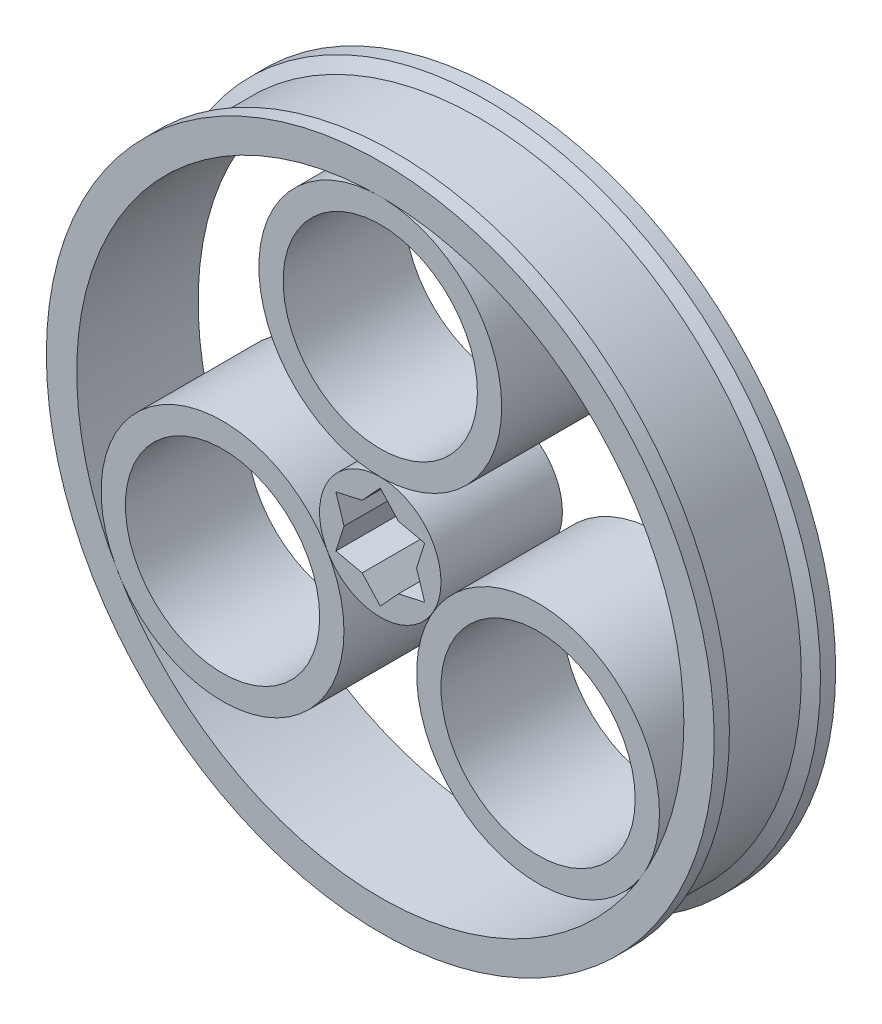
SolidWorks part; units mm, degrees
ref_plane "Front Plane" through (0, 0, 0) normal (0, 0, 1) x (1, 0, 0)
ref_plane "Top Plane" through (0, 0, 0) normal (0, 1, 0) x (1, 0, 0)
ref_plane "Right Plane" through (0, 0, 0) normal (1, 0, 0) x (0, 0, -1)
sketch "Sketch1" plane through (0, 0, 0) normal (0, 0, 1) x (1, 0, 0)
  circle A0 centre (0, 0) radius 27.5
  circle A1 centre (0, 0) radius 25
  circle A2 centre (0, 0) radius 5
  circle A3 centre (0, 15) radius 10
  circle A5 centre (0, 15) radius 8
  circle A6 centre (12.9904, -7.5) radius 10
  circle A7 centre (12.9904, -7.5) radius 8
  circle A8 centre (-12.9904, -7.5) radius 10
  circle A9 centre (-12.9904, -7.5) radius 8
  point P7 (0, 0)
  point P11 (0, 0)
  point P12 (0, 0)
  point P21 (0, 0)
  dimension "D1" = 55
  dimension "D2" = 50
  dimension "D3" = 10
  dimension "D4" = 2
  dimension "D5" = 3
extrude "Boss-Extrude1" add sketch "Sketch1" along normal blind 10 contours A3 A5 | A8 A9 | A6 A7 | A0 A1 | A2
sketch "Sketch2" plane through (0, 0, 0) normal (0, 0, -1) x (-1, 0, 0)
  line L0 (0, 0) -> (0, 5) construction
  line L1 (0, 3.9225) -> (-1.9538, 1.7903)
  line L2 (0, 3.9225) -> (1.9538, 1.7903)
  line L3 (3.397, 1.9612) -> (2.5273, -0.7969)
  line L4 (3.397, 1.9612) -> (0.5736, 2.5872)
  line L5 (3.397, -1.9612) -> (0.5736, -2.5872)
  line L6 (3.397, -1.9612) -> (2.5273, 0.7969)
  line L7 (0, -3.9225) -> (-1.9538, -1.7903)
  line L8 (0, -3.9225) -> (1.9538, -1.7903)
  line L9 (-3.397, -1.9612) -> (-2.5273, 0.7969)
  line L10 (-3.397, -1.9612) -> (-0.5736, -2.5872)
  line L11 (-3.397, 1.9612) -> (-0.5736, 2.5872)
  line L12 (-3.397, 1.9612) -> (-2.5273, -0.7969)
  circle A1 centre (0, 0) radius 2.65
  circle A2 centre (0, 15) radius 10 construction
  point P1 (-4.6486, -2.2417)
  point P13 (0, 0)
  point P28 (0, 0)
  dimension "D2" = 5.3
  dimension "D3" = 6
  dimension "D1" = 85
extrude "Cut-Extrude1" cut sketch "Sketch2" against normal blind 10
sketch "Sketch3" plane through (0, 0, 0) normal (1, 0, 0) x (0, 0, -1)
  line L0 (-10, -27.5) -> (0, -27.5) construction
  line L1 (-10, 27.5) -> (-8.75, 27.5) construction
  line L2 (-10, 27.5) -> (-10, -27.5) construction
  line L3 (-10, -27.5) -> (-8.75, -27.5) construction
  line L4 (-8.75, 27.5) -> (-8.75, -27.5) construction
  line L5 (-5, 27.5) -> (-5, -27.5) construction
  line L6 (0, 27.5) -> (-10, 27.5) construction
  line L7 (-1.25, 27.5) -> (-1.25, -27.5) construction
  line L8 (0, -27.5) -> (-1.25, -27.5) construction
  line L9 (0, 27.5) -> (0, -27.5) construction
  line L10 (0, 27.5) -> (-1.25, 27.5) construction
  line L11 (-8.75, 26.5) -> (-1.25, 26.5)
  line L12 (-8.75, 27.5) -> (-1.25, 27.5)
  line L13 (-8.75, 27.5) -> (-8.75, -27.5) construction
  line L14 (-8.75, -27.5) -> (-1.25, -27.5) construction
  line L15 (-1.25, 27.5) -> (-1.25, -27.5) construction
  line L16 (-5, 0) -> (-1.25, 0) construction
  line L17 (-8.75, 27.5) -> (-8.1726, 26.5)
  line L18 (-1.25, 27.5) -> (-1.8274, 26.5)
  dimension "D1" = 1.25
  dimension "D2" = 1
  dimension "D3" = 30
revolve "Cut-Revolve1" cut sketch "Sketch3" angle 360 about L16
sketch "Sketch5" plane through (0, 0, 0) normal (0, 0, -1) x (-1, 0, 0)
  line L35 (-3.6534, 2.1093) -> (-2.9883, 0)
  line L36 (3.6534, -2.1093) -> (2.9883, 0)
  line L37 (2.9883, 0) -> (3.6534, 2.1093)
  line L38 (3.6534, 2.1093) -> (1.4942, 2.588)
  line L39 (1.4942, 2.588) -> (0, 4.2185)
  line L40 (0, 4.2185) -> (-1.4942, 2.588)
  line L41 (-1.4942, 2.588) -> (-3.6534, 2.1093)
  line L42 (-2.9883, 0) -> (-3.6534, -2.1093)
  line L43 (-3.6534, -2.1093) -> (-1.4942, -2.588)
  line L44 (-1.4942, -2.588) -> (0, -4.2185)
  line L45 (0, -4.2185) -> (1.4942, -2.588)
  line L46 (1.4942, -2.588) -> (3.6534, -2.1093)
  line L47 (-3.6534, 2.1093) -> (-2.9883, 0)
  line L48 (3.6534, -2.1093) -> (2.9883, 0)
  line L49 (2.9883, 0) -> (3.6534, 2.1093)
  line L50 (3.6534, 2.1093) -> (1.4942, 2.588)
  line L51 (1.4942, 2.588) -> (0, 4.2185)
  line L52 (0, 4.2185) -> (-1.4942, 2.588)
  line L53 (-1.4942, 2.588) -> (-3.6534, 2.1093)
  line L54 (-2.9883, 0) -> (-3.6534, -2.1093)
  line L55 (-3.6534, -2.1093) -> (-1.4942, -2.588)
  line L56 (-1.4942, -2.588) -> (0, -4.2185)
  line L57 (0, -4.2185) -> (1.4942, -2.588)
  line L58 (1.4942, -2.588) -> (3.6534, -2.1093)
  dimension "D1" = 0.2
extrude "Cut-Extrude2" cut sketch "Sketch5" against normal up to surface (10 mm away) up to face at (5, 0, 10)
